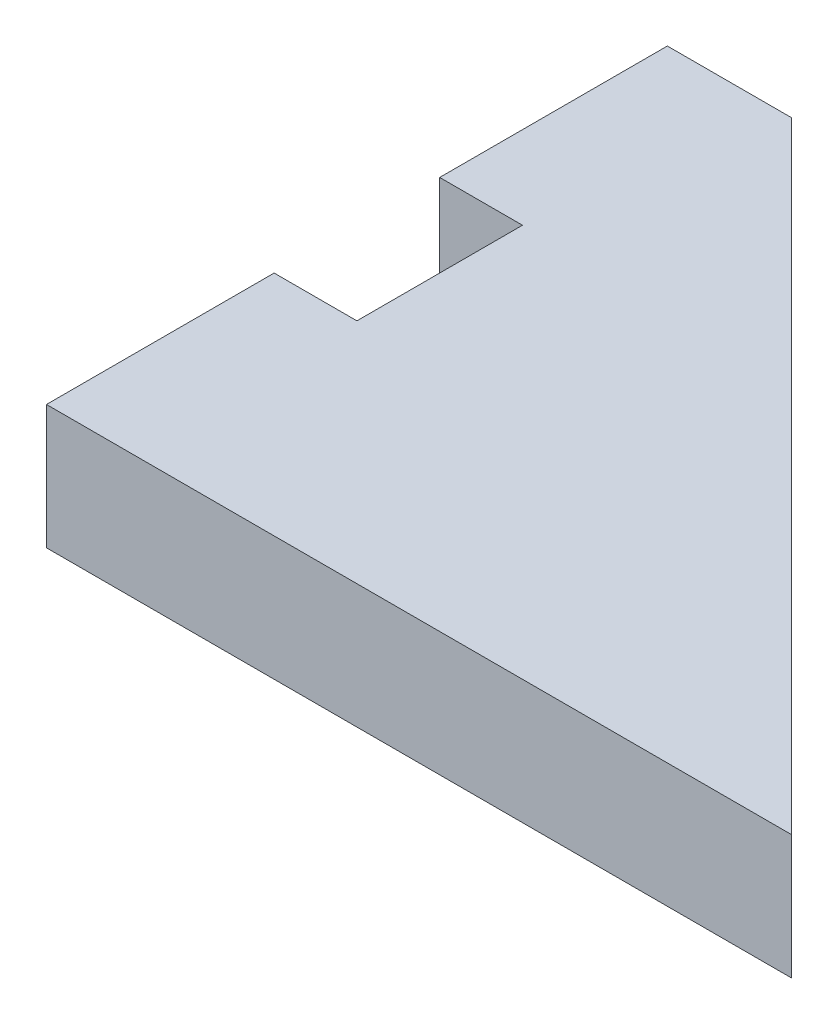
SolidWorks part; units mm, degrees
ref_plane "Front Plane" through (0, 0, 0) normal (0, 0, 1) x (1, 0, 0)
ref_plane "Top Plane" through (0, 0, 0) normal (0, 1, 0) x (1, 0, 0)
ref_plane "Right Plane" through (0, 0, 0) normal (1, 0, 0) x (0, 0, -1)
sketch "Sketch1" plane through (0, 0, 0) normal (0, 1, 0) x (1, 0, 0)
  line L0 (0, 0) -> (-1.5, 1.5)
  line L1 (-1.5, 1.5) -> (-1.8, 1.5)
  line L2 (-1.8, 1.5) -> (-1.8, 0.95)
  line L3 (-1.8, 0.95) -> (-1.6, 0.95)
  line L4 (-1.6, 0.95) -> (-1.6, 0.55)
  line L5 (-1.6, 0.55) -> (-1.8, 0.55)
  line L6 (-1.8, 0.55) -> (-1.8, 0)
  line L7 (-1.8, 0) -> (0, 0)
  point P3 (-1.6, 0.75)
  point P10 (-0.75, 0.75)
  dimension "D1" = 1.5
  dimension "D2" = 1.5
  dimension "D3" = 0.3
  dimension "D4" = 0.2
  dimension "D5" = 0.4
extrude "Boss-Extrude1" add sketch "Sketch1" along normal blind 0.3
equation "\"t\"= 0.3'thickness of the sheets"
equation "\"FlexJoint\"= 0.15'Width of flextures"
equation "\"FoldJoint\"= 0.4'Width of folding joints"
equation "\"AssembleAngle\"= 90'Angle of assembly parts"
equation "\"D1@Boss-Extrude1\"=\"t\""
